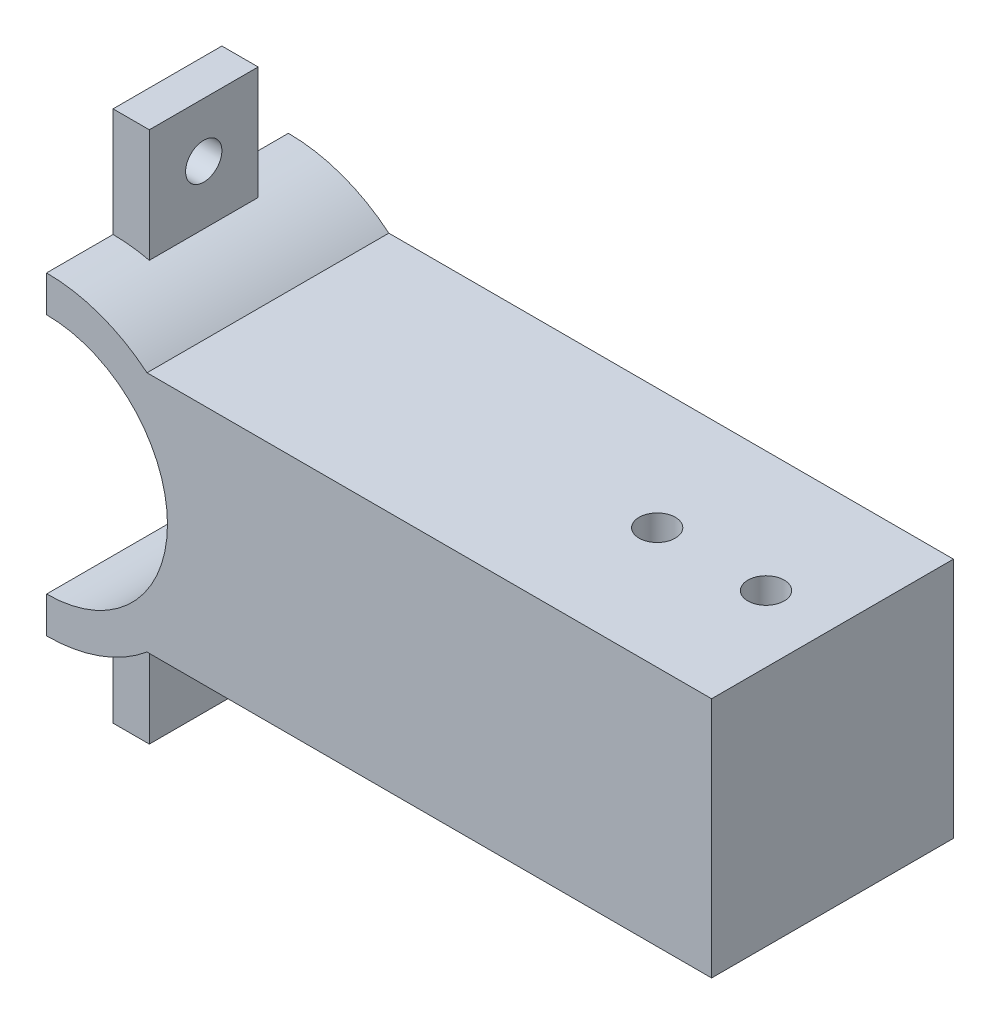
SolidWorks part; units mm, degrees
ref_plane "Спереди" through (0, 0, 0) normal (0, 0, 1) x (1, 0, 0)
ref_plane "Сверху" through (0, 0, 0) normal (0, 1, 0) x (1, 0, 0)
ref_plane "Справа" through (0, 0, 0) normal (1, 0, 0) x (0, 0, -1)
sketch "Эскиз1" plane through (0, 0, 0) normal (0, 0, 1) x (1, 0, 0)
  line L0 (0, 10) -> (0, 13)
  line L1 (0, -10) -> (0, -13)
  line L2 (0, 0) -> (10, 0) construction
  line L3 (0, 0) -> (0, -10) construction
  line L4 (55, -10) -> (8.3066, -10)
  line L5 (10, 0) -> (55, 0) construction
  line L6 (55, 0) -> (55, -10)
  line L11 (8.3066, 10) -> (55, 10)
  line L12 (55, 10) -> (55, 0)
  arc A0 (0, 10) -> (0, -10) centre (0, 0) cw
  arc A2 (0, 13) -> (8.3066, 10) centre (0, 0) cw
  arc A3 (0, -13) -> (8.3066, -10) centre (0, 0) ccw
  dimension "D1" = 10
  dimension "D4" = 46.6934
  dimension "D2" = 3
  dimension "D3" = 20
  dimension "D5" = 10
extrude "Бобышка-Вытянуть1" add sketch "Эскиз1" along normal blind 20
sketch "Эскиз2" plane through (0, 10, 0) normal (0, 1, 0) x (1, 0, 0)
  line L2 (40.5, -10) -> (45, -10) construction
  line L4 (45, -10) -> (45, 0) construction
  line L6 (45, -10) -> (49.5, -10) construction
  line L7 (55, 0) -> (8.3066, 0) construction
  line L8 (45, -10) -> (45, -20) construction
  line L9 (55, -20) -> (8.3066, -20) construction
  line L10 (55, -20) -> (55, 0) construction
  circle A0 centre (40.5, -10) radius 1.5
  circle A1 centre (49.5, -10) radius 1.5
  dimension "D1" = 3
  dimension "D2" = 4.5
  dimension "D3" = 10
sketch "Эскиз4" plane through (0, 10, 0) normal (0, 1, 0) x (1, 0, 0)
extrude "Вырез-Вытянуть1" cut sketch "Эскиз2" against normal through all
sketch "Эскиз6" plane through (0, 0, 0) normal (-1, 0, 0) x (0, 0, 1)
  line L0 (10, 10) -> (10, -10) construction
  line L1 (20, 10) -> (0, 10) construction
  line L2 (20, -10) -> (0, -10) construction
  line L3 (10, 10) -> (5.5, 10)
  line L4 (5.5, 10) -> (5.5, 22)
  line L5 (5.5, 22) -> (14.5, 22)
  line L6 (14.5, 22) -> (14.5, 10)
  line L7 (14.5, 10) -> (10, 10)
  line L8 (10, -10) -> (5.5, -10)
  line L9 (5.5, -10) -> (5.5, -22)
  line L10 (5.5, -22) -> (14.5, -22)
  line L11 (14.5, -22) -> (14.5, -10)
  line L12 (14.5, -10) -> (10, -10)
  circle A0 centre (10, 17.5) radius 1.5
  circle A1 centre (10, -17.5) radius 1.5
  point P18 (0, 0)
  dimension "D1" = 3
  dimension "D6" = 4.5
  dimension "D2" = 4.5
  dimension "D3" = 7.5
  dimension "D4" = 12
  dimension "D5" = 4.5
  dimension "D7" = 7.5
extrude "Бобышка-Вытянуть2" add sketch "Эскиз6" against normal blind 3
